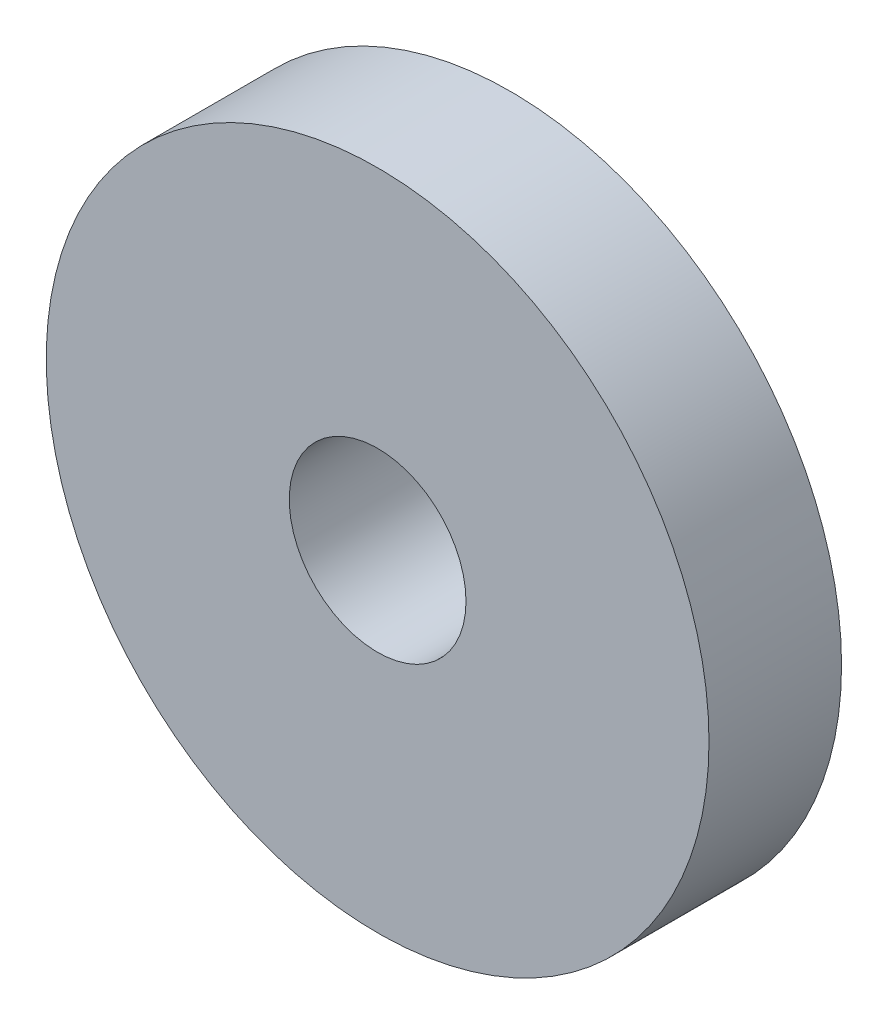
SolidWorks part; units mm, degrees
material "环氧树脂,未充填"
ref_plane "前视基准面" through (0, 0, 0) normal (0, 0, 1) x (1, 0, 0)
ref_plane "上视基准面" through (0, 0, 0) normal (0, 1, 0) x (1, 0, 0)
ref_plane "右视基准面" through (0, 0, 0) normal (1, 0, 0) x (0, 0, -1)
sketch "草图1" plane through (0, 0, 0) normal (0, 0, 1) x (1, 0, 0)
  circle A0 centre (0, 0) radius 7.5
  circle A1 centre (0, 0) radius 2
  dimension "D1" = 15
  dimension "D2" = 4
extrude "凸台-拉伸1" add sketch "草图1" along normal blind 3
